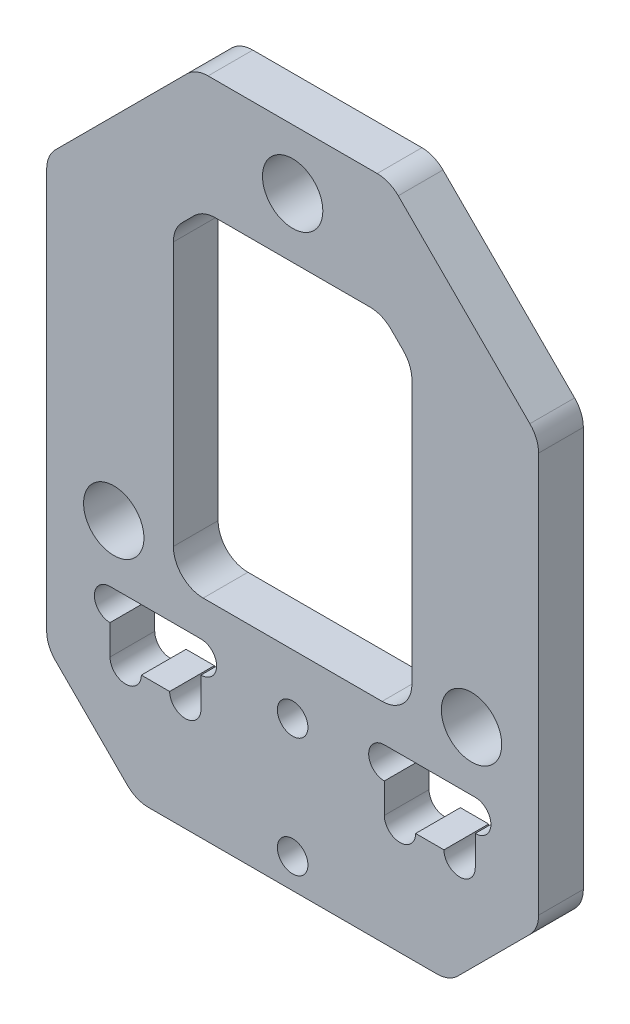
SolidWorks part; units mm, degrees
material "Thornel Mat VMA"
ref_plane "前视基准面" through (0, 0, 0) normal (0, 0, 1) x (1, 0, 0)
ref_plane "上视基准面" through (0, 0, 0) normal (0, 1, 0) x (1, 0, 0)
ref_plane "右视基准面" through (0, 0, 0) normal (1, 0, 0) x (0, 0, -1)
other "Configuration Table"
sketch "草图1" plane through (0, 0, 0) normal (0, 0, 1) x (1, 0, 0)
  line L1 (-16.5, -22.25) -> (16.5, -22.25)
  line L2 (-16.5, -22.25) -> (-16.5, 22.25)
  line L3 (-16.5, 22.25) -> (16.5, 22.25)
  line L4 (16.5, -22.25) -> (16.5, 22.25)
  line L5 (-16.5, -22.25) -> (16.5, 22.25) construction
  line L6 (-16.5, 22.25) -> (16.5, -22.25) construction
  point P0 (0, 0)
  dimension "D1" = 33
  dimension "D2" = 44.5
extrude "凸台-拉伸1" add sketch "草图1" along normal blind 3
sketch "草图2" plane through (0, 0, 3) normal (0, 0, 1) x (1, 0, 0)
  circle A0 centre (12, -6.75) radius 2.025 construction
  circle A1 centre (-12, -6.75) radius 2.025 construction
  circle A2 centre (0, 18.25) radius 2.025 construction
  circle A3 centre (12, -6.75) radius 2.025
  circle A4 centre (-12, -6.75) radius 2.025
  circle A5 centre (0, 18.25) radius 2.025
  circle A6 centre (0, -20.25) radius 0.8 construction
  circle A7 centre (0, -12.25) radius 0.8 construction
  circle A8 centre (0, -20.25) radius 0.8 construction
  circle A9 centre (0, -12.25) radius 0.8 construction
  circle A10 centre (0, -12.25) radius 1.025
  circle A11 centre (0, -20.25) radius 1.025
  dimension "D1" = 2.05
extrude "切除-拉伸1" cut sketch "草图2" against normal blind 13
chamfer "倒角1" distance 10 angle 45 2 edges at (16.5, 22.25, 1.5) (-16.5, 22.25, 1.5)
sketch "草图3" plane through (0, 0, 3) normal (0, 0, 1) x (1, 0, 0)
  line L0 (-8, -8.25) -> (8, -8.25)
  line L1 (8, -8.25) -> (8, 12.2647)
  line L2 (8, 12.2647) -> (6.0147, 14.25)
  line L3 (6.0147, 14.25) -> (-6.0147, 14.25)
  line L4 (-6.0147, 14.25) -> (-8, 12.2647)
  line L5 (-8, 12.2647) -> (-8, -8.25)
  line L6 (0, 0) -> (0, -8.25) construction
  line L7 (16.5, 12.25) -> (6.5, 22.25) construction
  line L8 (-6.5, 22.25) -> (-16.5, 12.25) construction
  circle A0 centre (12, -6.75) radius 2.025 construction
  circle A1 centre (0, -12.25) radius 1.025 construction
  circle A2 centre (0, 18.25) radius 2.025 construction
  dimension "D1" = 4
  dimension "D2" = 4
  dimension "D3" = 4
  dimension "D4" = 6
  dimension "D5" = 6
extrude "切除-拉伸2" cut sketch "草图3" against normal blind 13
fillet "圆角1" radius 2 6 edges at (-8, 12.2647, 1.5) (-6.0147, 14.25, 1.5) (6.0147, 14.25, 1.5) (8, 12.2647, 1.5) (8, -8.25, 1.5) (-8, -8.25, 1.5)
chamfer "倒角2" distance 6 angle 45 2 edges at (16.5, -22.25, 1.5) (-16.5, -22.25, 1.5)
fillet "圆角2" radius 2 8 edges at (6.5, 22.25, 1.5) (-6.5, 22.25, 1.5) (-16.5, 12.25, 1.5) (16.5, 12.25, 1.5) (16.5, -16.25, 1.5) (10.5, -22.25, 1.5) (-16.5, -16.25, 1.5) (-10.5, -22.25, 1.5)
sketch "草图4" plane through (0, 0, 3) normal (0, 0, 1) x (1, 0, 0)
  line L0 (-12.2, -10.75) -> (-6.2, -10.75) construction
  line L1 (-6.2, -10.75) -> (-6.2, -14.75) construction
  line L2 (-6.2, -14.75) -> (-12.2, -14.75) construction
  line L3 (-12.2, -14.75) -> (-12.2, -10.75) construction
  line L4 (6.2, -14.75) -> (6.2, -10.75) construction
  line L5 (6.2, -10.75) -> (12.2, -10.75) construction
  line L6 (12.2, -10.75) -> (12.2, -14.75) construction
  line L7 (12.2, -14.75) -> (6.2, -14.75) construction
  line L8 (-12.2, -10.75) -> (-6.2, -10.75) construction
  line L9 (-6.2, -10.75) -> (-6.2, -14.75) construction
  line L10 (-6.2, -14.75) -> (-12.2, -14.75) construction
  line L11 (-12.2, -14.75) -> (-12.2, -10.75) construction
  line L12 (6.2, -14.75) -> (6.2, -10.75) construction
  line L13 (6.2, -10.75) -> (12.2, -10.75) construction
  line L14 (12.2, -10.75) -> (12.2, -14.75) construction
  line L15 (12.2, -14.75) -> (6.2, -14.75) construction
  line L16 (-12.25, -10.7) -> (-6.15, -10.7)
  line L17 (-6.15, -10.7) -> (-6.15, -14.8)
  line L18 (-6.15, -14.8) -> (-12.25, -14.8)
  line L19 (-12.25, -14.8) -> (-12.25, -10.7)
  line L20 (6.15, -14.8) -> (6.15, -10.7)
  line L21 (6.15, -10.7) -> (12.25, -10.7)
  line L22 (12.25, -10.7) -> (12.25, -14.8)
  line L23 (12.25, -14.8) -> (6.15, -14.8)
  dimension "D1" = 0.05
extrude "切除-拉伸3" cut sketch "草图4" against normal up to surface (3 mm away) up to face at (0, 6.2476, 0)
sketch "草图5" plane through (0, 0, 3) normal (0, 0, 1) x (1, 0, 0)
  line L0 (-12.25, -14.8) -> (-6.15, -14.8) construction
  line L1 (6.15, -14.8) -> (12.25, -14.8) construction
  line L2 (-12.25, -10.7) -> (-12.25, -14.8) construction
  line L3 (-6.15, -14.8) -> (-6.15, -10.7) construction
  line L4 (6.15, -10.7) -> (6.15, -14.8) construction
  line L5 (12.25, -14.8) -> (12.25, -10.7) construction
  circle A0 centre (-11.2, -14.8) radius 1.05
  circle A1 centre (-7.2, -14.8) radius 1.05
  circle A2 centre (7.2, -14.8) radius 1.05
  circle A3 centre (11.2, -14.8) radius 1.05
  circle A4 centre (-12.25, -11.75) radius 1.05
  circle A5 centre (-6.15, -11.75) radius 1.05
  circle A6 centre (6.15, -11.75) radius 1.05
  circle A7 centre (12.25, -11.75) radius 1.05
  dimension "D1" = 2.1
extrude "切除-拉伸4" cut sketch "草图5" against normal up to surface (3 mm away) up to face at (-9.2, -12.75, 0)
